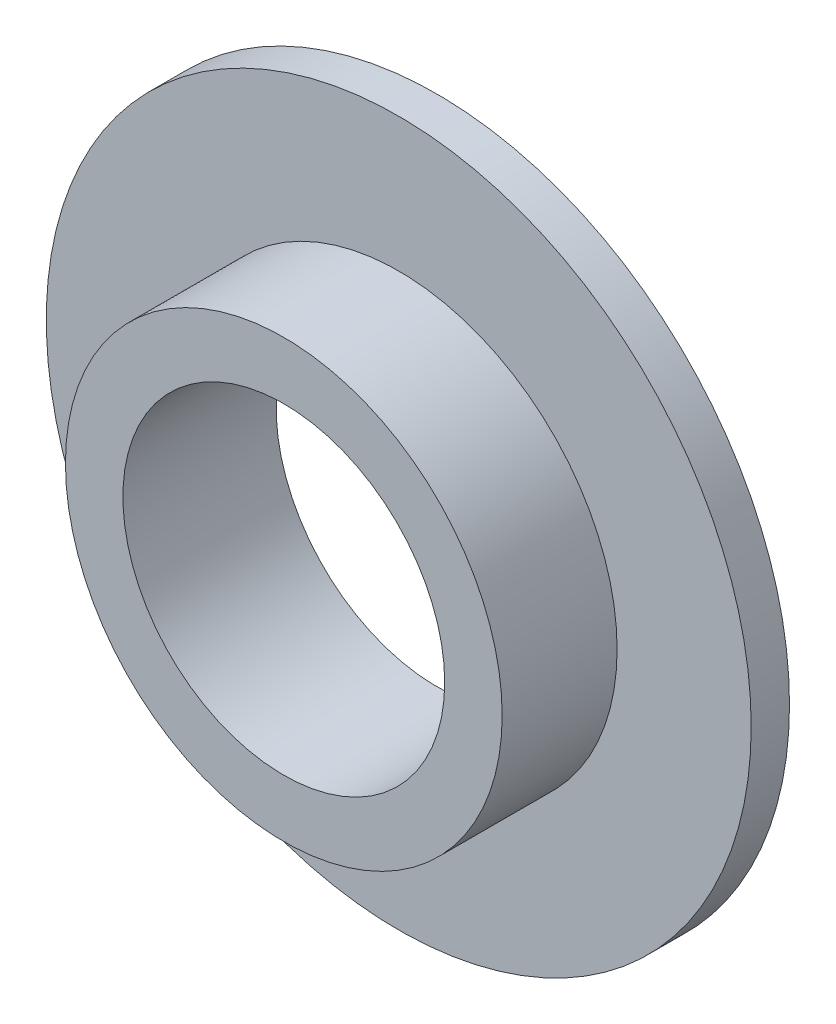
SolidWorks part; units mm, degrees
ref_plane "Alzado" through (0, 0, 0) normal (0, 0, 1) x (1, 0, 0)
ref_plane "Planta" through (0, 0, 0) normal (0, 1, 0) x (1, 0, 0)
ref_plane "Vista lateral" through (0, 0, 0) normal (1, 0, 0) x (0, 0, -1)
sketch "Croquis1" plane through (0, 0, 0) normal (0, 0, 1) x (1, 0, 0)
  circle A0 centre (0, 0) radius 8.4
  circle A1 centre (0, 0) radius 18.4
  dimension "D1" = 16.8
  dimension "D2" = 10
extrude "Saliente-Extruir1" add sketch "Croquis1" along normal mid plane 2
sketch "Croquis2" plane through (0, 0, 1) normal (0, 0, 1) x (1, 0, 0)
  circle A0 centre (0, 0) radius 8.4 construction
  circle A1 centre (0, 0) radius 8.4
  circle A2 centre (0, 0) radius 11.4
  dimension "D1" = 3
extrude "Saliente-Extruir2" add sketch "Croquis2" along normal blind 6
